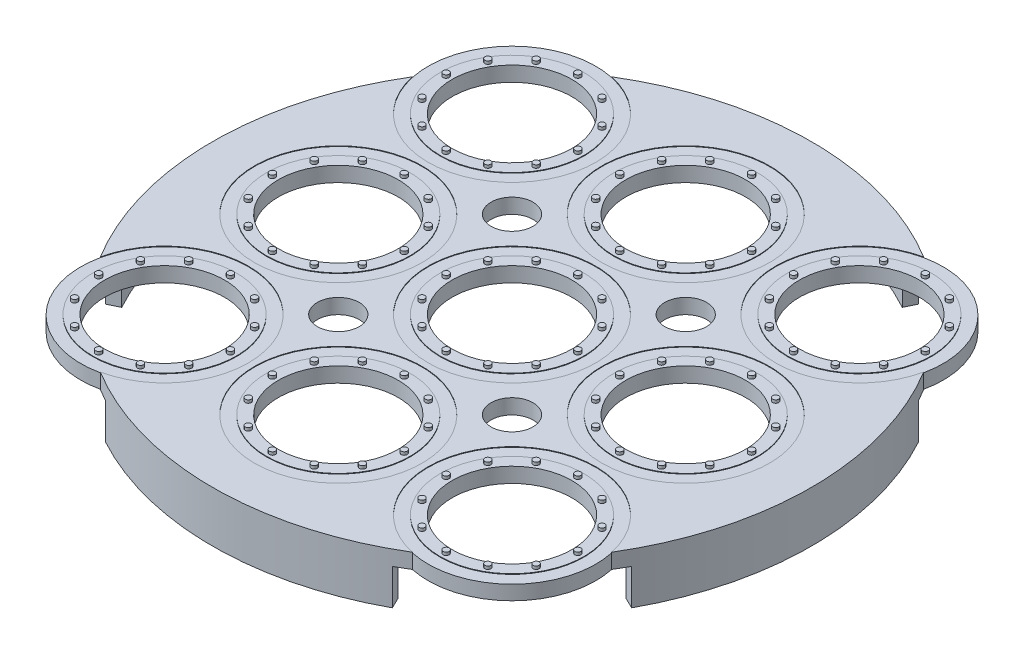
SolidWorks part; units mm, degrees
ref_plane "Front Plane" through (0, 0, 0) normal (0, 0, 1) x (1, 0, 0)
ref_plane "Top Plane" through (0, 0, 0) normal (0, 1, 0) x (1, 0, 0)
ref_plane "Right Plane" through (0, 0, 0) normal (1, 0, 0) x (0, 0, -1)
sketch "Sketch1" plane through (0, 0, 0) normal (0, 1, 0) x (1, 0, 0)
  arc A0 (26.0405, 42.6836) -> (-26.0405, 42.6836) centre (0, 0) ccw
  circle A1 centre (0, 0) radius 14 construction
  circle A2 centre (29, 0) radius 14 construction
  circle A3 centre (-29, 0) radius 14 construction
  arc A4 (26.0405, -42.6836) -> (42.6836, -26.0405) centre (29, -29) ccw
  circle A5 centre (0, -29) radius 14 construction
  arc A6 (-42.6836, -26.0405) -> (-26.0405, -42.6836) centre (-29, -29) ccw
  arc A7 (42.6836, 26.0405) -> (26.0405, 42.6836) centre (29, 29) ccw
  circle A8 centre (0, 29) radius 14 construction
  arc A9 (-26.0405, 42.6836) -> (-42.6836, 26.0405) centre (-29, 29) ccw
  arc A10 (-42.6836, 26.0405) -> (-42.6836, -26.0405) centre (0, 0) ccw
  arc A11 (-26.0405, -42.6836) -> (26.0405, -42.6836) centre (0, 0) ccw
  arc A12 (42.6836, -26.0405) -> (42.6836, 26.0405) centre (0, 0) ccw
  dimension "D1" = 100
  dimension "D2" = 28
  dimension "D5" = 29
  dimension "D8" = 29
  dimension "D3" = 29
  dimension "D4" = 29
  dimension "D6" = 3
  dimension "D7" = 2
extrude "Boss-Extrude1" add sketch "Sketch1" along normal blind 2.5
sketch "Sketch2" plane through (0, 2.5, 0) normal (0, 1, 0) x (1, 0, 0)
  circle A1 centre (-29, -29) radius 10
  dimension "D1" = 29
  dimension "D3" = 20
  dimension "D2" = 29
extrude "Cut-Extrude1" cut sketch "Sketch2" against normal through all
pattern_linear "LPattern1" count 3 spacing 29 along (1, 0, 0) count 3 spacing 29 along (0, 0, -1) of "Cut-Extrude1"
sketch "Sketch4" plane through (0, 2.5, 0) normal (0, 1, 0) x (1, 0, 0)
  circle A1 centre (-29, -29) radius 10 construction
  circle A2 centre (-29, -29) radius 10 construction
  circle A3 centre (-29, -18) radius 0.5
  dimension "D1" = 1
  dimension "D2" = 11
extrude "Boss-Extrude2" add sketch "Sketch4" along normal blind 0.5 contours A3
pattern_circular "CirPattern1" count 12 over 360 about axis through (-29, 0, 29) along (0, 1, 0) of "Boss-Extrude2"
pattern_linear "LPattern2" count 3 spacing 29 along (0, 0, -1) count 3 spacing 29 along (1, 0, 0) of "Boss-Extrude2", "CirPattern1"
sketch "Sketch5" plane through (0, 2.5, 0) normal (0, 1, 0) x (1, 0, 0)
  circle A0 centre (14.5, -14.5) radius 3.5
  circle A1 centre (29, 0) radius 10 construction
  circle A2 centre (0, -29) radius 10 construction
  dimension "D1" = 14.5
  dimension "D3" = 7
  dimension "D2" = 14.5
extrude "Cut-Extrude2" cut sketch "Sketch5" against normal through all contours A0
mirror "Mirror1" about plane through (0, 0, 0) normal (1, 0, 0) of "Cut-Extrude2"
mirror "Mirror2" about plane through (0, 0, 0) normal (0, 0, 1) of "Mirror1", "Cut-Extrude2"
sketch "Sketch6" plane through (0, 0, 0) normal (0, -1, 0) x (-1, 0, 0)
  line L0 (-23.9246, -43.9046) -> (-23.0478, -42.107)
  line L1 (23.9246, -43.9046) -> (23.0478, -42.107)
  arc A1 (-26.0405, -42.6836) -> (26.0405, -42.6836) centre (0, 0) ccw construction
  arc A2 (-23.0478, -42.107) -> (23.0478, -42.107) centre (0, 0) ccw
  arc A3 (-23.9246, -43.9046) -> (23.9246, -43.9046) centre (0, 0) ccw
  point P3 (0, -50)
  point P10 (0, -48.0021)
  dimension "D2" = 52
  dimension "D1" = 2
extrude "Boss-Extrude3" add sketch "Sketch6" along normal blind 6
pattern_circular "CirPattern2" count 4 over 360 about axis through (0, 0, 0) along (0, 1, 0) of "Boss-Extrude3"
sketch "Sketch7" plane through (0, 2.5, 0) normal (0, 1, 0) x (1, 0, 0)
  circle A0 centre (-29, -29) radius 14
  circle A1 centre (-29, -29) radius 12
  dimension "D1" = 28
  dimension "D2" = 24
extrude "Cut-Extrude3" cut sketch "Sketch7" against normal blind 0.1
pattern_linear "LPattern3" count 3 spacing 29 along (1, 0, 0) count 3 spacing 29 along (0, 0, -1) of "Cut-Extrude3"
